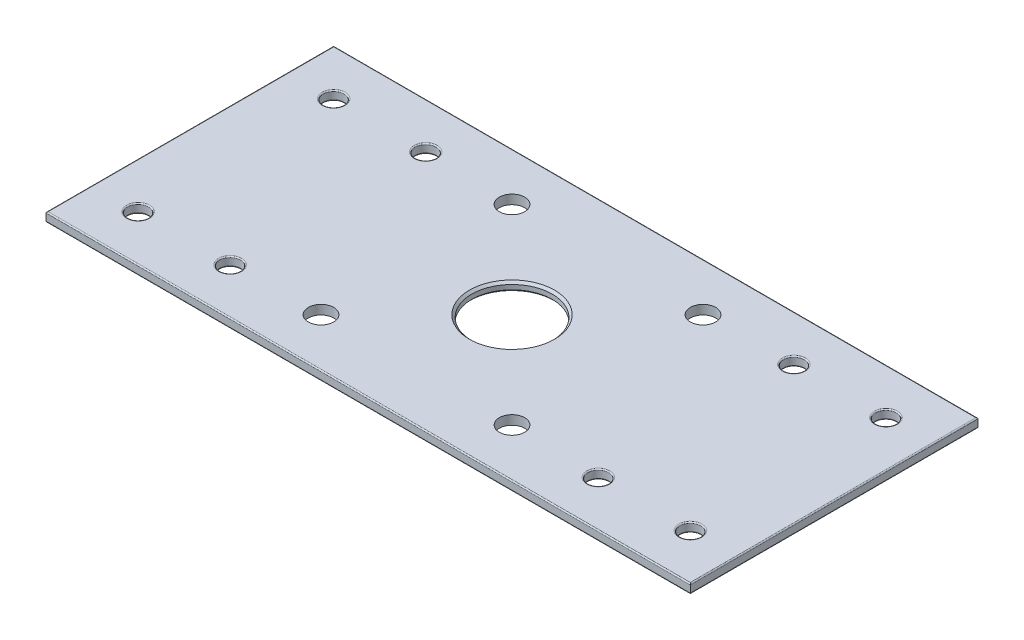
SolidWorks part; units mm, degrees
material "3.3549 (EN-AW 5182)"
ref_plane "Płaszczyzna przednia" through (0, 0, 0) normal (0, 0, 1) x (1, 0, 0)
ref_plane "Płaszczyzna górna" through (0, 0, 0) normal (0, 1, 0) x (1, 0, 0)
ref_plane "Płaszczyzna prawa" through (0, 0, 0) normal (1, 0, 0) x (0, 0, -1)
sketch "Szkic1" plane through (0, 0, 0) normal (0, 1, 0) x (1, 0, 0)
  line L1 (-140, -62.5) -> (140, -62.5)
  line L2 (-140, -62.5) -> (-140, 62.5)
  line L3 (-140, 62.5) -> (140, 62.5)
  line L4 (140, -62.5) -> (140, 62.5)
  line L5 (-140, -62.5) -> (140, 62.5) construction
  line L6 (-140, 62.5) -> (140, -62.5) construction
  point P0 (0, 0)
  dimension "D1" = 280
  dimension "D2" = 125
extrude "Dodanie-wyciągnięcie1" add sketch "Szkic1" along normal blind 4
sketch "Szkic2" plane through (0, 4, 0) normal (0, 1, 0) x (1, 0, 0)
  line L0 (140, -62.5) -> (140, 62.5) construction
  line L1 (-140, -62.5) -> (140, -62.5) construction
  line L2 (220.873, 0) -> (-232.9418, 0) construction
  line L3 (0, 140.8418) -> (0, -183.3116) construction
  circle A0 centre (120, -42.5) radius 4
  circle A1 centre (80, -42.5) radius 4
  circle A2 centre (-80, -42.5) radius 4
  circle A3 centre (-120, -42.5) radius 4
  circle A4 centre (120, 42.5) radius 4
  circle A5 centre (80, 42.5) radius 4
  circle A6 centre (-80, 42.5) radius 4
  circle A7 centre (-120, 42.5) radius 4
  dimension "D1" = 20
  dimension "D2" = 20
  dimension "D3" = 8
  dimension "D4" = 8
  dimension "D5" = 40
hole_wizard "Otwór pod śrubę M81" positions "Szkic3" profile "Szkic4" hole size "M8" standard "ISO"
sketch "Szkic3" plane through (0, 4, 0) normal (0, 1, 0) x (1, 0, 0)
  point P0 (-120, 42.5)
  point P3 (-80, 42.5)
  point P6 (-80, -42.5)
  point P9 (-120, -42.5)
  point P12 (120, -42.5)
  point P15 (80, -42.5)
  point P18 (80, 42.5)
  point P21 (120, 42.5)
sketch "Szkic4" plane through (-120, 4, -42.5) normal (1, 0, 0) x (0, 0, 1)
  line L0 (0, 0) -> (0, 12.7039)
  line L1 (0, 12.7039) -> (4.5, 10)
  line L2 (4.5, 10) -> (4.5, 0)
  line L5 (4.5, 0) -> (0, 0)
  line L10 (0, 12.7039) -> (-4.5, 10) construction
  line L11 (0, -6.35) -> (0, 107.95) construction
  dimension "Średnica otworu" = 9
  dimension "Głębokość otworu" = 10
  dimension "Kąt wiertła" = 118
fillet "Zaokrąglenie1" radius 0.5 24 edges at (0, 0, -62.5) (-140, 0, 0) (0, 0, 62.5) (140, 0, 0) (120, 0, -47) (80, 0, -47) (80, 0, 38) (120, 0, 38) (-120, 0, 38) (-80, 0, 38) (-80, 0, -47) (-120, 0, -47) (0, 4, 62.5) (-140, 4, 0) (0, 4, -62.5) (140, 4, 0) (120, 4, -38) (80, 4, -38) (80, 4, 47) (120, 4, 47) (-120, 4, 47) (-80, 4, 47) (-80, 4, -38) (-120, 4, -38)
sketch "Szkic5" plane through (0, 4, 0) normal (0, 1, 0) x (1, 0, 0)
  line L0 (0, -2.2) -> (0, 2.2) construction
  line L1 (-41.5, -41.5) -> (41.5, -41.5)
  line L2 (-41.5, -41.5) -> (-41.5, 41.5)
  line L3 (-41.5, 41.5) -> (41.5, 41.5)
  line L4 (41.5, -41.5) -> (41.5, 41.5)
  line L5 (-41.5, -41.5) -> (41.5, 41.5) construction
  line L6 (-41.5, 41.5) -> (41.5, -41.5) construction
  line L7 (-2.2, 0) -> (2.2, 0) construction
  circle A0 centre (0, 0) radius 17.5
  circle A1 centre (41.5, 41.5) radius 5
  circle A2 centre (-41.5, 41.5) radius 5
  circle A3 centre (41.5, -41.5) radius 5
  circle A4 centre (-41.5, -41.5) radius 5
  dimension "D1" = 35
  dimension "D4" = 10
  dimension "D2" = 83
  dimension "D3" = 83
hole_wizard "Otwór pod śrubę M101" positions "Szkic6" profile "Szkic7" hole size "M10" standard "ISO"
sketch "Szkic6" plane through (0, 4, 0) normal (0, 1, 0) x (1, 0, 0)
  point P0 (41.5, 41.5)
  point P3 (-41.5, 41.5)
  point P6 (-41.5, -41.5)
  point P9 (41.5, -41.5)
sketch "Szkic7" plane through (41.5, 4, -41.5) normal (1, 0, 0) x (0, 0, 1)
  line L0 (0, 0) -> (0, 13.3047)
  line L1 (0, 13.3047) -> (5.5, 10)
  line L2 (5.5, 10) -> (5.5, 0)
  line L5 (5.5, 0) -> (0, 0)
  line L10 (0, 13.3047) -> (-5.5, 10) construction
  line L11 (0, -6.35) -> (0, 107.95) construction
  dimension "Średnica otworu" = 11
  dimension "Głębokość otworu" = 10
  dimension "Kąt wiertła" = 118
extrude "Wytnij-wyciągnięcie1" cut sketch "Szkic5" against normal blind 4 contours A0
chamfer "Sfazowanie1" distance 1 angle 45 2 edges at (0, 0, 17.5) (0, 4, 17.5)
